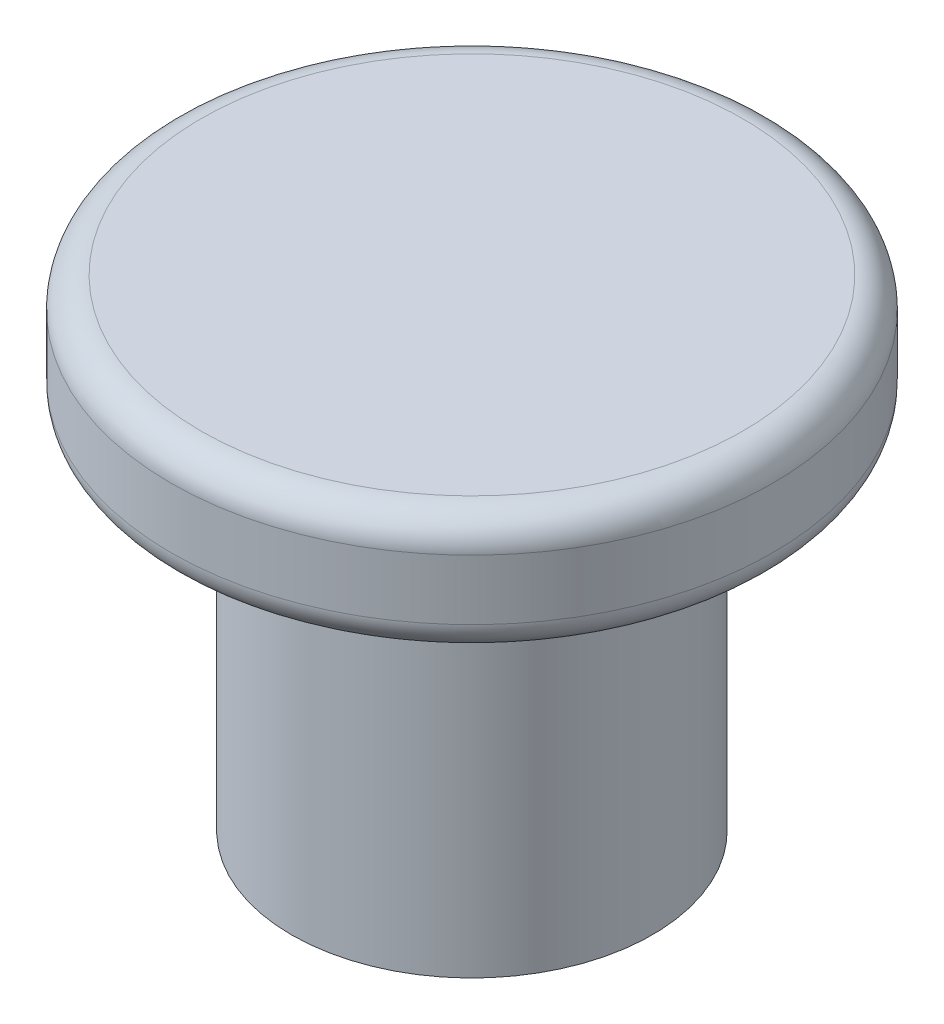
SolidWorks part; units mm, degrees
ref_plane "Front Plane" through (0, 0, 0) normal (0, 0, 1) x (1, 0, 0)
ref_plane "Top Plane" through (0, 0, 0) normal (0, 1, 0) x (1, 0, 0)
ref_plane "Right Plane" through (0, 0, 0) normal (1, 0, 0) x (0, 0, -1)
sketch "Sketch1" plane through (0, 0, 0) normal (0, 1, 0) x (1, 0, 0)
  circle A0 centre (0, 0) radius 2.5
  dimension "D1" = 5
extrude "Boss-Extrude1" add sketch "Sketch1" along normal blind 1
fillet "Fillet1" radius 0.25 2 edges at (0, 0, 2.5) (0, 1, 2.5)
sketch "Sketch2" plane through (0, 0, 0) normal (0, -1, 0) x (1, 0, 0)
  circle A0 centre (0, 0) radius 1.5
  dimension "D1" = 3
extrude "Boss-Extrude2" add sketch "Sketch2" along normal blind 3
hole_wizard "1/16 (0.07874016) Diameter Hole1" positions "Sketch5" profile "Sketch4" hole size "1/16" standard "ANSI Inch"
sketch "Sketch5" plane through (0, -3, 0) normal (0, -1, 0) x (-1, 0, 0)
  point P0 (0, 0)
sketch "Sketch4" plane through (0, -3, 0) normal (1, 0, 0) x (0, 0, -1)
  line L0 (0, 0) -> (0, 2.3509)
  line L1 (0, 2.3509) -> (1, 1.75)
  line L2 (1, 1.75) -> (1, 0)
  line L5 (1, 0) -> (0, 0)
  line L10 (0, 2.3509) -> (-1, 1.75) construction
  line L11 (0, -6.35) -> (0, 107.95) construction
  dimension "Hole Dia." = 2
  dimension "Hole Depth" = 1.75
  dimension "Drill Angle" = 118
fillet "Fillet2" radius 0.15 1 edges at (0, -3, -1)
